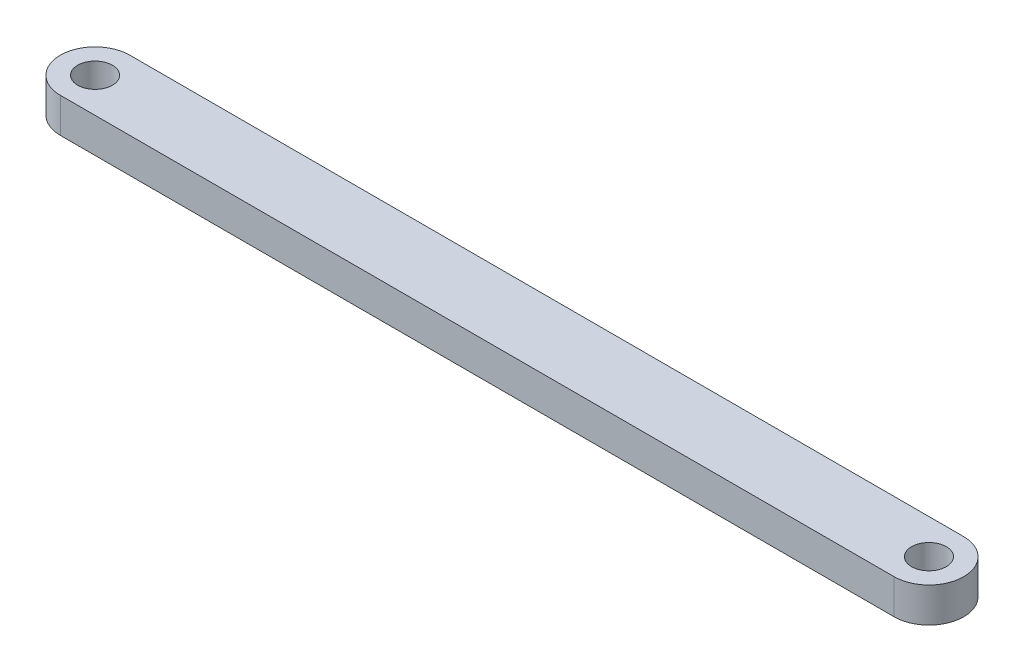
SolidWorks part; units mm, degrees
ref_plane "Front Plane" through (0, 0, 0) normal (0, 0, 1) x (1, 0, 0)
ref_plane "Top Plane" through (0, 0, 0) normal (0, 1, 0) x (1, 0, 0)
ref_plane "Right Plane" through (0, 0, 0) normal (1, 0, 0) x (0, 0, -1)
sketch "Sketch1" plane through (0, 0, 0) normal (0, 1, 0) x (1, 0, 0)
  line L1 (60, -5) -> (-60, -5)
  line L3 (60, 5) -> (-60, 5)
  arc A0 (-60, 5) -> (-60, -5) centre (-60, 0) ccw
  circle A1 centre (-60, 0) radius 2.5
  arc A2 (60, -5) -> (60, 5) centre (60, 0) ccw
  circle A3 centre (60, 0) radius 2.5
  point P0 (0, 0)
  dimension "D1" = 10
  dimension "D2" = 5
  dimension "D3" = 120
extrude "Boss-Extrude1" add sketch "Sketch1" along normal blind 5
